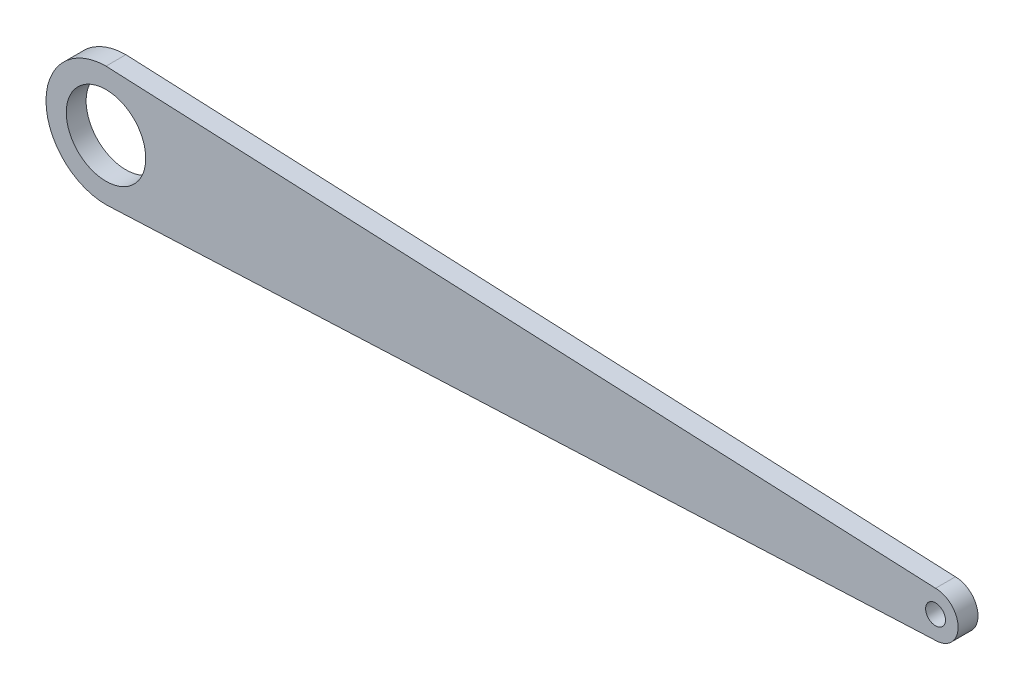
SolidWorks part; units mm, degrees
ref_plane "Plano frontal" through (0, 0, 0) normal (0, 0, 1) x (1, 0, 0)
ref_plane "Plano superior" through (0, 0, 0) normal (0, 1, 0) x (1, 0, 0)
ref_plane "Plano direito" through (0, 0, 0) normal (1, 0, 0) x (0, 0, -1)
sketch "Esboço1" plane through (0, 0, 0) normal (0, 0, 1) x (1, 0, 0)
  line L1 (-35.0265, 0) -> (35.0265, 0) construction
  line L3 (-35.0265, 0) -> (-35.0265, -15.0988) construction
  line L8 (-35.0265, 15.0988) -> (173.7135, 5.6851)
  line L9 (-35.0265, -15.0988) -> (173.7135, -5.6851)
  circle A2 centre (-35.0265, 0) radius 10
  arc A3 (-35.0265, -15.0988) -> (-35.0265, 15.0988) centre (-35.0265, 0) cw
  circle A5 centre (173.7135, 0) radius 2.5
  arc A6 (173.7135, 5.6851) -> (173.7135, -5.6851) centre (173.7135, 0) cw
  point P3 (0, 0)
  dimension "D1" = 208.74
extrude "Ressalto-extrusão1" add sketch "Esboço1" along normal blind 5
